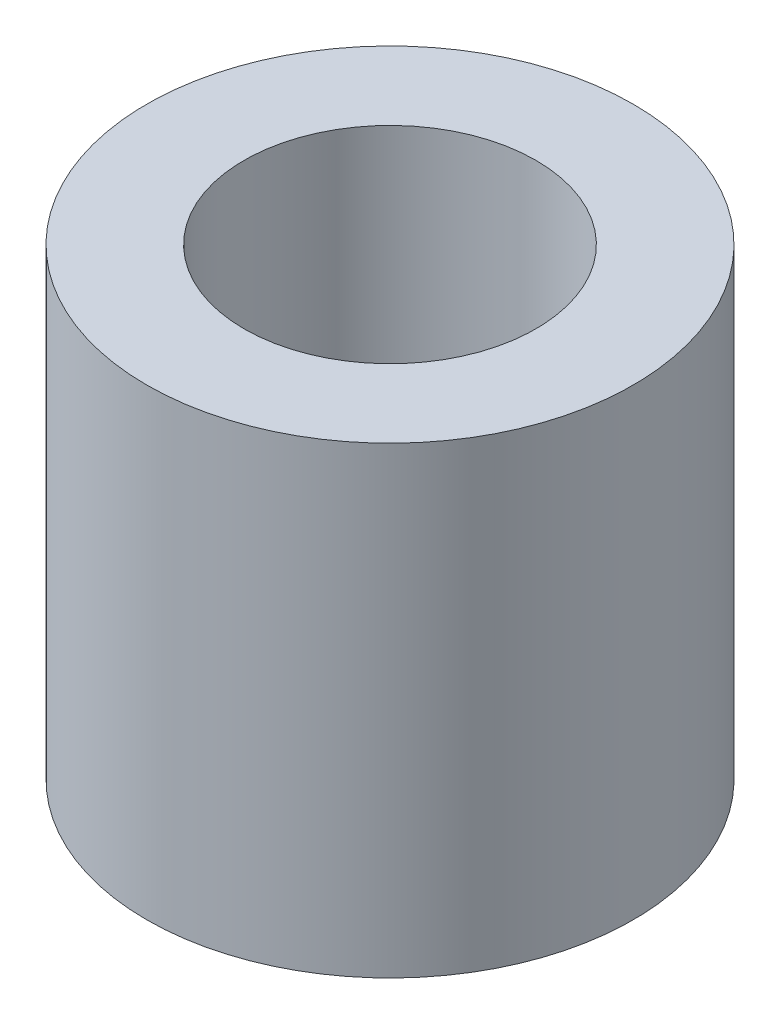
SolidWorks part; units mm, degrees
ref_plane "Front Plane" through (0, 0, 0) normal (0, 0, 1) x (1, 0, 0)
ref_plane "Top Plane" through (0, 0, 0) normal (0, 1, 0) x (1, 0, 0)
ref_plane "Right Plane" through (0, 0, 0) normal (1, 0, 0) x (0, 0, -1)
sketch "Sketch1" plane through (0, 0, 0) normal (0, 1, 0) x (1, 0, 0)
  circle A0 centre (0, 0) radius 1.5
  circle A1 centre (0, 0) radius 2.5
  dimension "D1" = 3
  dimension "D2" = 5
extrude "Boss-Extrude1" add sketch "Sketch1" along normal blind 4.76
